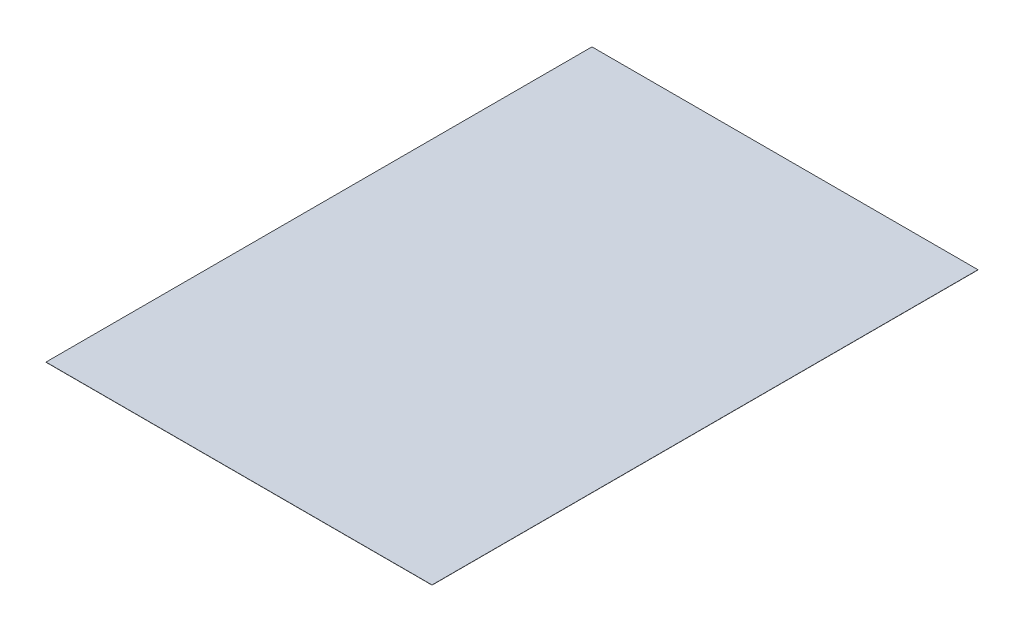
SolidWorks part; units mm, degrees
ref_plane "Front Plane" through (0, 0, 0) normal (0, 0, 1) x (1, 0, 0)
ref_plane "Top Plane" through (0, 0, 0) normal (0, 1, 0) x (1, 0, 0)
ref_plane "Right Plane" through (0, 0, 0) normal (1, 0, 0) x (0, 0, -1)
sketch "Esquisse1" plane through (0, 0, 0) normal (0, 1, 0) x (1, 0, 0)
  line L1 (0, 0) -> (210, 0)
  line L2 (0, 0) -> (0, 297)
  line L3 (0, 297) -> (210, 297)
  line L4 (210, 0) -> (210, 297)
  dimension "D1" = 297
  dimension "D2" = 210
extrude "Boss.-Extru.1" add sketch "Esquisse1" along normal blind 0.1
